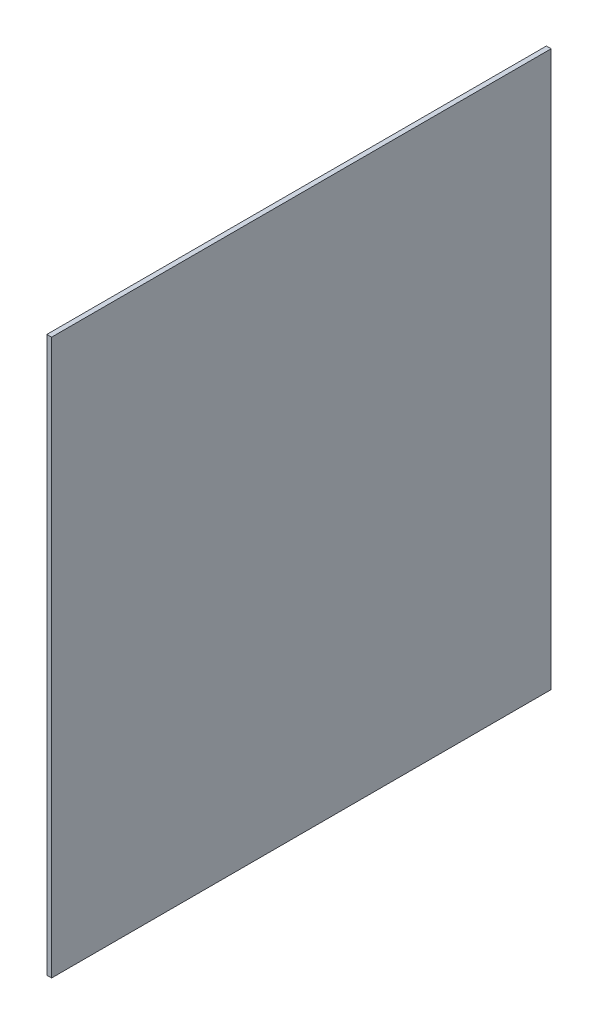
SolidWorks part; units mm, degrees
ref_plane "前视基准面" through (0, 0, 0) normal (0, 0, 1) x (1, 0, 0)
ref_plane "上视基准面" through (0, 0, 0) normal (0, 1, 0) x (1, 0, 0)
ref_plane "右视基准面" through (0, 0, 0) normal (1, 0, 0) x (0, 0, -1)
sketch "草图1" plane through (0, 0, 0) normal (1, 0, 0) x (0, 0, -1)
  line L1 (0, 0) -> (315, 0)
  line L2 (0, 0) -> (0, 350)
  line L3 (0, 350) -> (315, 350)
  line L4 (315, 0) -> (315, 350)
  dimension "D1" = 350
  dimension "D2" = 315
extrude "凸台-拉伸1" add sketch "草图1" along normal blind 3
